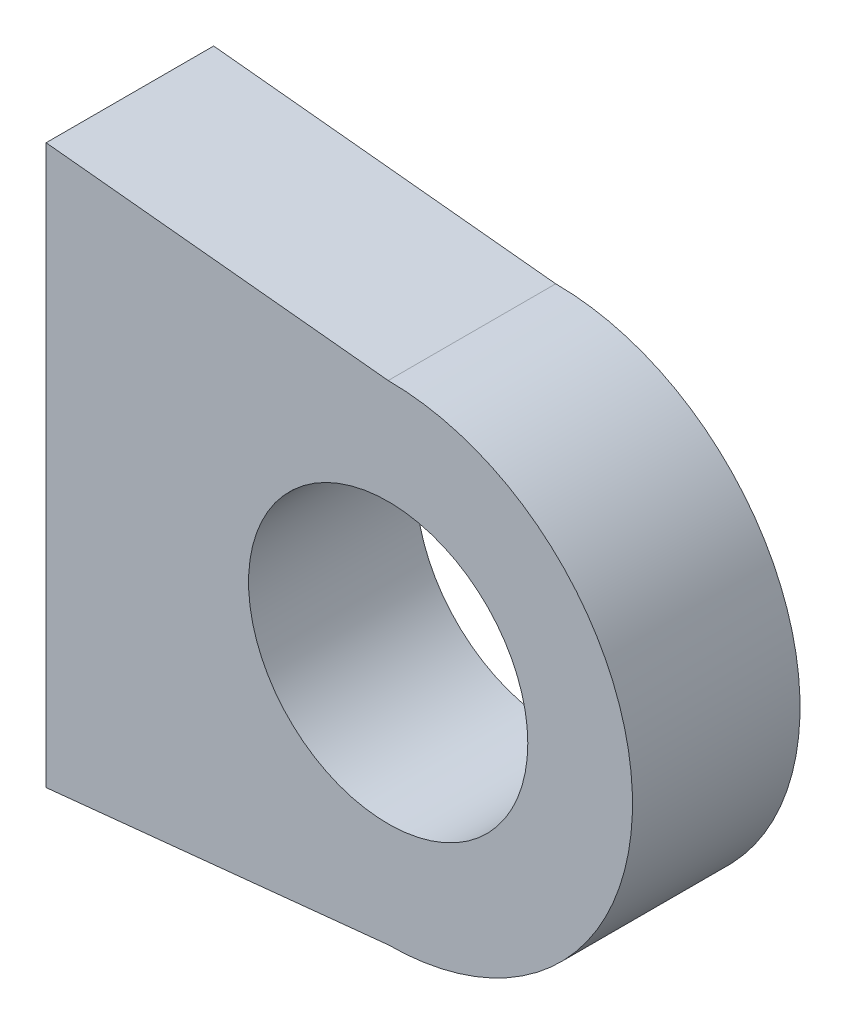
SolidWorks part; units mm, degrees
ref_plane "Front Plane" through (0, 0, 0) normal (0, 0, 1) x (1, 0, 0)
ref_plane "Top Plane" through (0, 0, 0) normal (0, 1, 0) x (1, 0, 0)
ref_plane "Right Plane" through (0, 0, 0) normal (1, 0, 0) x (0, 0, -1)
sketch "Sketch1" plane through (0, 0, 0) normal (0, 0, 1) x (1, 0, 0)
  line L0 (0, 0) -> (0, 10)
  line L1 (0, 0) -> (0, -10)
  line L2 (0, 0) -> (12.25, 0) construction
  line L3 (0, 10) -> (12.25, 8.75)
  line L4 (0, -10) -> (12.25, -8.75)
  arc A0 (12.25, -8.75) -> (12.25, 8.75) centre (12.25, 0) ccw
  circle A1 centre (12.25, 0) radius 5
  dimension "D4" = 17.5
  dimension "D5" = 10
  dimension "D1" = 10
  dimension "D2" = 10
  dimension "D3" = 12.25
extrude "Boss-Extrude1" add sketch "Sketch1" along normal blind 6
sketch "Sketch2" plane through (0, 0, 0) normal (-1, 0, 0) x (0, 0, 1)
  line L0 (0, 0) -> (6, 0) construction
  line L1 (6, 10) -> (6, -10) construction
  line L2 (3, 0) -> (3, 7.1) construction
  line L3 (3, 0) -> (3, -7.1) construction
  circle A0 centre (3, 7.1) radius 1.35
  circle A1 centre (3, -7.1) radius 1.35
  circle A2 centre (3, 0) radius 2
  dimension "D2" = 2.7
  dimension "D4" = 2.7
  dimension "D5" = 4
  dimension "D1" = 7.1
  dimension "D3" = 7.1
extrude "Cut-Extrude1" cut sketch "Sketch2" against normal blind 3
